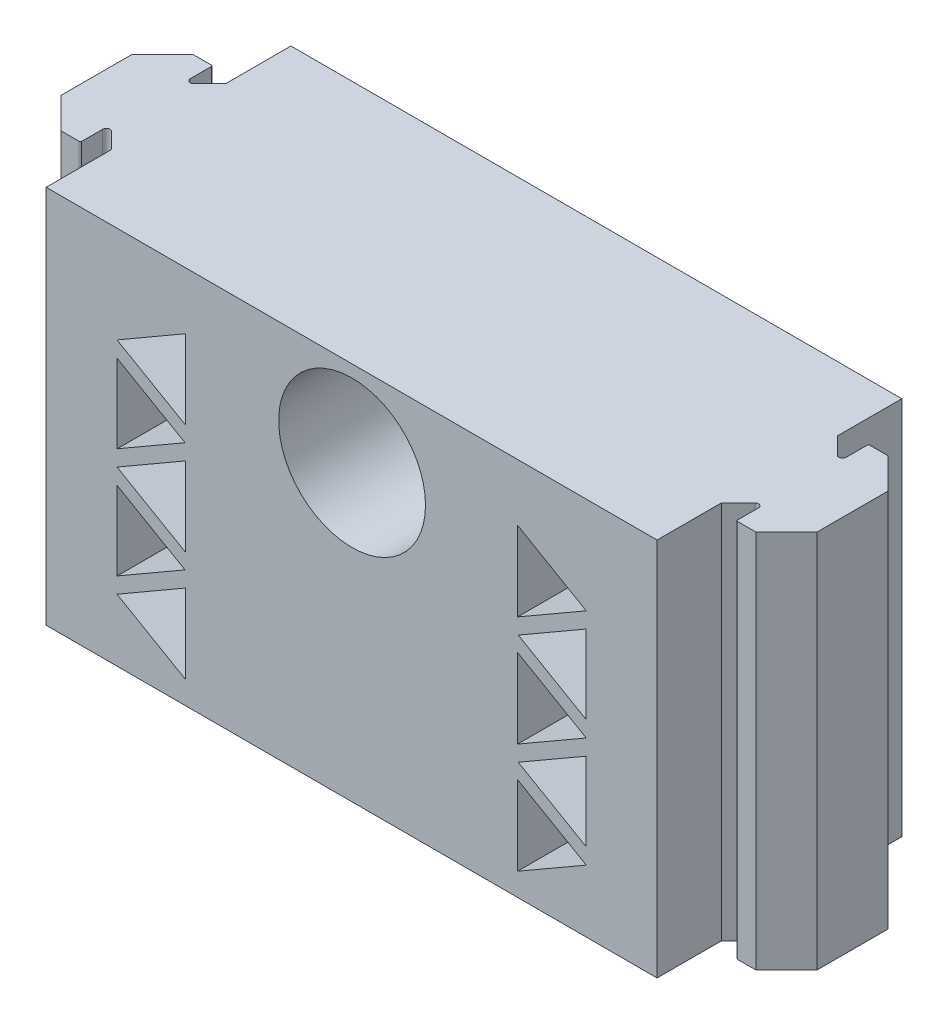
SolidWorks part; units mm, degrees
ref_plane "Plan de face" through (0, 0, 0) normal (0, 0, 1) x (1, 0, 0)
ref_plane "Plan de dessus" through (0, 0, 0) normal (0, 1, 0) x (1, 0, 0)
ref_plane "Plan de droite" through (0, 0, 0) normal (1, 0, 0) x (0, 0, -1)
sketch "Esquisse1" plane through (0, 0, 0) normal (0, 1, 0) x (1, 0, 0)
  line L0 (0, 10) -> (0, -10) construction
  line L5 (30.5607, 5.5) -> (25, 5.5) construction
  line L6 (31.1414, 0) -> (25, 0) construction
  line L10 (-25, -10) -> (-25, -4.6586)
  line L11 (29.5, -5.5) -> (29.5, 5.5) construction
  line L12 (29.5, -5.5) -> (25, -5.5) construction
  line L13 (30.9293, 0.2121) -> (30.8293, 0.3121)
  line L14 (31.1414, 0) -> (30.9293, 0.2121)
  line L15 (30.9293, -0.2121) -> (31.1414, 0)
  line L16 (30.9293, -0.2121) -> (30.8293, -0.3121)
  line L17 (26.2879, -3.3707) -> (24.9293, -4.7293)
  line L18 (26.8, -3.5828) -> (26.8, -5.3)
  line L19 (28.3979, -5.4) -> (26.9, -5.4)
  line L20 (28.3979, -5.4) -> (30.9, -2.8979)
  line L21 (30.9, -2.8979) -> (30.9, 2.8979)
  line L22 (28.3979, 5.4) -> (30.9, 2.8979)
  line L23 (26.9, 5.4) -> (28.3979, 5.4)
  line L24 (-31, -2.9393) -> (-31, 2.9393)
  line L25 (26.8, 3.5828) -> (26.8, 5.3)
  line L26 (24.9293, 4.7293) -> (26.2879, 3.3707)
  line L27 (26.3586, -3.4414) -> (25, -4.8)
  line L28 (26.7, -3.5828) -> (26.7, -5.3)
  line L29 (28.4393, -5.5) -> (26.9, -5.5)
  line L30 (28.4393, -5.5) -> (31, -2.9393)
  line L31 (28.4393, 5.5) -> (31, 2.9393)
  line L32 (26.9, 5.5) -> (28.4393, 5.5)
  line L33 (26.7, 3.5828) -> (26.7, 5.3)
  line L34 (25, 4.8) -> (26.3586, 3.4414)
  line L35 (31, -2.9393) -> (31, 2.9393)
  line L36 (24.9293, 4.7293) -> (24.9293, 10)
  line L37 (24.9293, -4.7293) -> (24.9293, -10)
  line L38 (-25, 4.6586) -> (-25, 10)
  line L39 (-29.5, 0) -> (-31.1414, 0) construction
  line L44 (-25, 4.8) -> (-26.3586, 3.4414)
  line L45 (-26.7, 3.5828) -> (-26.7, 5.3)
  line L46 (-26.9, 5.5) -> (-28.4393, 5.5)
  line L47 (-28.4393, 5.5) -> (-31, 2.9393)
  line L56 (-28.4393, -5.5) -> (-31, -2.9393)
  line L57 (-28.4393, -5.5) -> (-26.9, -5.5)
  line L58 (-26.7, -3.5828) -> (-26.7, -5.3)
  line L59 (-26.3586, -3.4414) -> (-25, -4.8)
  line L78 (-24.9293, 4.7293) -> (-26.2879, 3.3707)
  line L79 (-26.8, 3.5828) -> (-26.8, 5.3)
  line L80 (-26.9, 5.4) -> (-28.3979, 5.4)
  line L81 (-28.3979, 5.4) -> (-30.9, 2.8979)
  line L82 (-30.9, -2.8979) -> (-30.9, 2.8979)
  line L83 (-28.3979, -5.4) -> (-30.9, -2.8979)
  line L84 (-28.3979, -5.4) -> (-26.9, -5.4)
  line L85 (-26.8, -3.5828) -> (-26.8, -5.3)
  line L86 (-26.2879, -3.3707) -> (-24.9293, -4.7293)
  line L108 (-30.9293, -0.2121) -> (-30.8293, -0.3121)
  line L109 (-30.9293, -0.2121) -> (-31.1414, 0)
  line L110 (-31.1414, 0) -> (-30.9293, 0.2121)
  line L111 (-30.9293, 0.2121) -> (-30.8293, 0.3121)
  line L112 (35, 0) -> (0, 0) construction
  line L113 (-25, -7.1429) -> (24.9293, 7.1227) construction
  line L114 (-26.7, -8.3) -> (-25, -10) construction
  line L115 (-26.7, -8.3) -> (-25, -8.3) construction
  line L116 (-25, -10) -> (24.9293, -10)
  line L121 (-29.5, -5.5) -> (-25, -5.5) construction
  line L122 (-29.5, -5.5) -> (-29.5, 5.5) construction
  line L125 (-31, -4) -> (-27.2222, -7.7778) construction
  line L127 (-31.1414, 0) -> (-29.5, 0) construction
  line L128 (-27.2222, 7.7778) -> (-25, 10) construction
  line L129 (-30.5607, 5.5) -> (-25, 5.5) construction
  line L131 (-25, 10) -> (24.9293, 10)
  line L132 (-27.2222, 7.7778) -> (24.9293, -7.1227) construction
  arc A1 (26.8, -3.5828) -> (26.2879, -3.3707) centre (26.5, -3.5828) ccw
  arc A2 (26.9, -5.4) -> (26.8, -5.3) centre (26.9, -5.3) cw
  arc A3 (-26.7, -3.5828) -> (-26.3586, -3.4414) centre (-26.5, -3.5828) cw
  arc A4 (-26.3586, 3.4414) -> (-26.7, 3.5828) centre (-26.5, 3.5828) cw
  arc A5 (26.8, 5.3) -> (26.9, 5.4) centre (26.9, 5.3) cw
  arc A6 (26.2879, 3.3707) -> (26.8, 3.5828) centre (26.5, 3.5828) ccw
  arc A7 (26.9, -5.5) -> (26.7, -5.3) centre (26.9, -5.3) cw
  arc A8 (26.7, 5.3) -> (26.9, 5.5) centre (26.9, 5.3) cw
  arc A9 (26.3586, 3.4414) -> (26.7, 3.5828) centre (26.5, 3.5828) ccw
  arc A10 (26.7, -3.5828) -> (26.3586, -3.4414) centre (26.5, -3.5828) ccw
  arc A11 (-26.7, 5.3) -> (-26.9, 5.5) centre (-26.9, 5.3) ccw
  arc A12 (-26.9, -5.5) -> (-26.7, -5.3) centre (-26.9, -5.3) ccw
  arc A25 (-26.2879, 3.3707) -> (-26.8, 3.5828) centre (-26.5, 3.5828) cw
  arc A26 (-26.8, 5.3) -> (-26.9, 5.4) centre (-26.9, 5.3) ccw
  arc A27 (-26.9, -5.4) -> (-26.8, -5.3) centre (-26.9, -5.3) ccw
  arc A28 (-26.8, -3.5828) -> (-26.2879, -3.3707) centre (-26.5, -3.5828) cw
  point P0 (0, 0)
extrude "Boss.-Extru.1" add sketch "Esquisse1" along normal blind 24
sketch "Esquisse3" plane through (0, 0, 10) normal (0, 0, 1) x (1, 0, 0)
  line L0 (0, 0) -> (-0.0354, 24) construction
  line L1 (-25, 24) -> (24.9293, 24) construction
  line L2 (-30.9, 17) -> (30.9, 17) construction
  line L3 (-30.9, 24) -> (-30.9, 0) construction
  line L4 (30.9, 24) -> (30.9, 0) construction
  line L5 (-25, 0) -> (24.9293, 0) construction
  circle A0 centre (0, 17) radius 6
  dimension "D2" = 12
  dimension "D1" = 17
extrude "Enlèv. mat.-Extru.2" cut sketch "Esquisse3" against normal through all
sketch "Esquisse5" plane through (0, 0, 0) normal (0, -1, 0) x (1, 0, 0)
  line L24 (-25, -4.6586) -> (-25, -10)
  line L25 (-25, -10) -> (24.9293, -10)
  line L26 (24.9293, -10) -> (24.9293, -4.7293)
  line L27 (24.9293, -4.7293) -> (26.2879, -3.3707)
  line L28 (26.8, -3.5828) -> (26.8, -5.3)
  line L29 (26.9, -5.4) -> (28.3979, -5.4)
  line L30 (28.3979, -5.4) -> (30.9, -2.8979)
  line L31 (30.9, -2.8979) -> (30.9, 2.8979)
  line L32 (30.9, 2.8979) -> (28.3979, 5.4)
  line L33 (28.3979, 5.4) -> (26.9, 5.4)
  line L34 (26.8, 5.3) -> (26.8, 3.5828)
  line L35 (26.2879, 3.3707) -> (24.9293, 4.7293)
  line L36 (24.9293, 4.7293) -> (24.9293, 10)
  line L37 (24.9293, 10) -> (-25, 10)
  line L38 (-25, 10) -> (-25, 4.6586)
  line L39 (-25, 4.6586) -> (-26.2879, 3.3707)
  line L40 (-26.8, 3.5828) -> (-26.8, 5.3)
  line L41 (-26.9, 5.4) -> (-28.3979, 5.4)
  line L42 (-28.3979, 5.4) -> (-30.9, 2.8979)
  line L43 (-30.9, 2.8979) -> (-30.9, -2.8979)
  line L44 (-30.9, -2.8979) -> (-28.3979, -5.4)
  line L45 (-28.3979, -5.4) -> (-26.9, -5.4)
  line L46 (-26.8, -5.3) -> (-26.8, -3.5828)
  line L47 (-26.2879, -3.3707) -> (-25, -4.6586)
  line L48 (-25, -4.6586) -> (-25, -10)
  line L49 (-25, -10) -> (24.9293, -10)
  line L50 (24.9293, -10) -> (24.9293, -4.7293)
  line L51 (24.9293, -4.7293) -> (26.2879, -3.3707)
  line L52 (26.8, -3.5828) -> (26.8, -5.3)
  line L53 (26.9, -5.4) -> (28.3979, -5.4)
  line L54 (28.3979, -5.4) -> (30.9, -2.8979)
  line L55 (30.9, -2.8979) -> (30.9, 2.8979)
  line L56 (30.9, 2.8979) -> (28.3979, 5.4)
  line L57 (28.3979, 5.4) -> (26.9, 5.4)
  line L58 (26.8, 5.3) -> (26.8, 3.5828)
  line L59 (26.2879, 3.3707) -> (24.9293, 4.7293)
  line L60 (24.9293, 4.7293) -> (24.9293, 10)
  line L61 (24.9293, 10) -> (-25, 10)
  line L62 (-25, 10) -> (-25, 4.6586)
  line L63 (-25, 4.6586) -> (-26.2879, 3.3707)
  line L64 (-26.8, 3.5828) -> (-26.8, 5.3)
  line L65 (-26.9, 5.4) -> (-28.3979, 5.4)
  line L66 (-28.3979, 5.4) -> (-30.9, 2.8979)
  line L67 (-30.9, 2.8979) -> (-30.9, -2.8979)
  line L68 (-30.9, -2.8979) -> (-28.3979, -5.4)
  line L69 (-28.3979, -5.4) -> (-26.9, -5.4)
  line L70 (-26.8, -5.3) -> (-26.8, -3.5828)
  line L71 (-26.2879, -3.3707) -> (-25, -4.6586)
  arc A8 (26.8, -3.5828) -> (26.2879, -3.3707) centre (26.5, -3.5828) ccw
  arc A9 (26.8, -5.3) -> (26.9, -5.4) centre (26.9, -5.3) ccw
  arc A10 (26.9, 5.4) -> (26.8, 5.3) centre (26.9, 5.3) ccw
  arc A11 (26.2879, 3.3707) -> (26.8, 3.5828) centre (26.5, 3.5828) ccw
  arc A12 (-26.8, 3.5828) -> (-26.2879, 3.3707) centre (-26.5, 3.5828) ccw
  arc A13 (-26.8, 5.3) -> (-26.9, 5.4) centre (-26.9, 5.3) ccw
  arc A14 (-26.9, -5.4) -> (-26.8, -5.3) centre (-26.9, -5.3) ccw
  arc A15 (-26.2879, -3.3707) -> (-26.8, -3.5828) centre (-26.5, -3.5828) ccw
  arc A16 (26.8, -3.5828) -> (26.2879, -3.3707) centre (26.5, -3.5828) ccw
  arc A17 (26.8, -5.3) -> (26.9, -5.4) centre (26.9, -5.3) ccw
  arc A18 (26.9, 5.4) -> (26.8, 5.3) centre (26.9, 5.3) ccw
  arc A19 (26.2879, 3.3707) -> (26.8, 3.5828) centre (26.5, 3.5828) ccw
  arc A20 (-26.8, 3.5828) -> (-26.2879, 3.3707) centre (-26.5, 3.5828) ccw
  arc A21 (-26.8, 5.3) -> (-26.9, 5.4) centre (-26.9, 5.3) ccw
  arc A22 (-26.9, -5.4) -> (-26.8, -5.3) centre (-26.9, -5.3) ccw
  arc A23 (-26.2879, -3.3707) -> (-26.8, -3.5828) centre (-26.5, -3.5828) ccw
  dimension "D1" = 0
extrude "Boss.-Extru.2" add sketch "Esquisse5" along normal blind 7
sketch "Esquisse6" plane through (0, 0, 10) normal (0, 0, 1) x (1, 0, 0)
  line L0 (-0.0354, -7) -> (-0.0354, 24) construction
  line L1 (24.9293, -7) -> (-25, -7) construction
  line L2 (-19.1978, 5.7981) -> (-19.1978, -0.6069)
  line L3 (-30.9, 8.5) -> (30.9, 8.5) construction
  line L4 (-30.9, 24) -> (-30.9, -7) construction
  line L5 (30.9, 24) -> (30.9, -7) construction
  line L6 (-61.7646, 24) -> (-30.9, 24) construction
  line L7 (-15.4677, 24) -> (-15.4677, -7) construction
  line L8 (-0.0354, 24) -> (30.8293, 24) construction
  line L9 (15.397, 24) -> (15.397, -7) construction
  line L10 (-13.5976, 10.3377) -> (-19.2114, 7.0924)
  line L11 (-19.2114, -1.9076) -> (-13.594, -5.1466)
  line L12 (-13.594, -5.1466) -> (-13.5976, 1.3377)
  line L13 (-13.5976, 1.3377) -> (-19.2114, -1.9076)
  line L14 (-19.2114, 7.0924) -> (-13.594, 3.8534)
  line L15 (-13.594, 3.8534) -> (-13.5976, 10.3377)
  line L16 (-13.5976, 19.3377) -> (-19.2114, 16.0924)
  line L17 (-19.2114, 16.0924) -> (-13.594, 12.8534)
  line L18 (-13.594, 12.8534) -> (-13.5976, 19.3377)
  line L19 (-19.1978, 8.3931) -> (-13.6509, 11.5956)
  line L20 (-13.6509, 11.5956) -> (-19.1978, 14.7981)
  line L21 (-19.1978, 14.7981) -> (-19.1978, 8.3931)
  line L22 (-13.6509, 2.5956) -> (-19.1978, 5.7981)
  line L23 (-19.1978, -0.6069) -> (-13.6509, 2.5956)
  line L24 (19.1271, -0.6069) -> (13.5802, 2.5956)
  line L25 (13.5802, 2.5956) -> (19.1271, 5.7981)
  line L26 (19.1271, 14.7981) -> (19.1271, 8.3931)
  line L27 (13.5802, 11.5956) -> (19.1271, 14.7981)
  line L28 (19.1271, 8.3931) -> (13.5802, 11.5956)
  line L29 (13.5233, 12.8534) -> (13.5269, 19.3377)
  line L30 (19.1407, 16.0924) -> (13.5233, 12.8534)
  line L31 (13.5269, 19.3377) -> (19.1407, 16.0924)
  line L32 (13.5233, 3.8534) -> (13.5269, 10.3377)
  line L33 (19.1407, 7.0924) -> (13.5233, 3.8534)
  line L34 (13.5269, 1.3377) -> (19.1407, -1.9076)
  line L35 (13.5233, -5.1466) -> (13.5269, 1.3377)
  line L36 (19.1407, -1.9076) -> (13.5233, -5.1466)
  line L37 (13.5269, 10.3377) -> (19.1407, 7.0924)
  line L38 (19.1271, 5.7981) -> (19.1271, -0.6069)
  circle A0 centre (-15.4677, -1.9055) radius 1.8719 construction
  circle A1 centre (-15.4677, 7.0945) radius 1.8719 construction
  circle A2 centre (-15.4677, 16.0945) radius 1.8719 construction
  circle A3 centre (-17.3694, 11.6341) radius 1.849 construction
  circle A4 centre (-17.3694, 2.6341) radius 1.849 construction
  circle A5 centre (17.2987, 2.6341) radius 1.849 construction
  circle A6 centre (17.2987, 11.6341) radius 1.849 construction
  circle A7 centre (15.397, 16.0945) radius 1.8719 construction
  circle A8 centre (15.397, 7.0945) radius 1.8719 construction
  circle A9 centre (15.397, -1.9055) radius 1.8719 construction
  point P44 (-9.5375, 11.1887)
  dimension "D3" = 1.259
  dimension "D4" = 1.259
  dimension "D1" = 3
  dimension "D2" = 2
extrude "Enlèv. mat.-Extru.3" cut sketch "Esquisse6" against normal through all
equation "\"D4@Esquisse6\"=\"D3@Esquisse6\""
